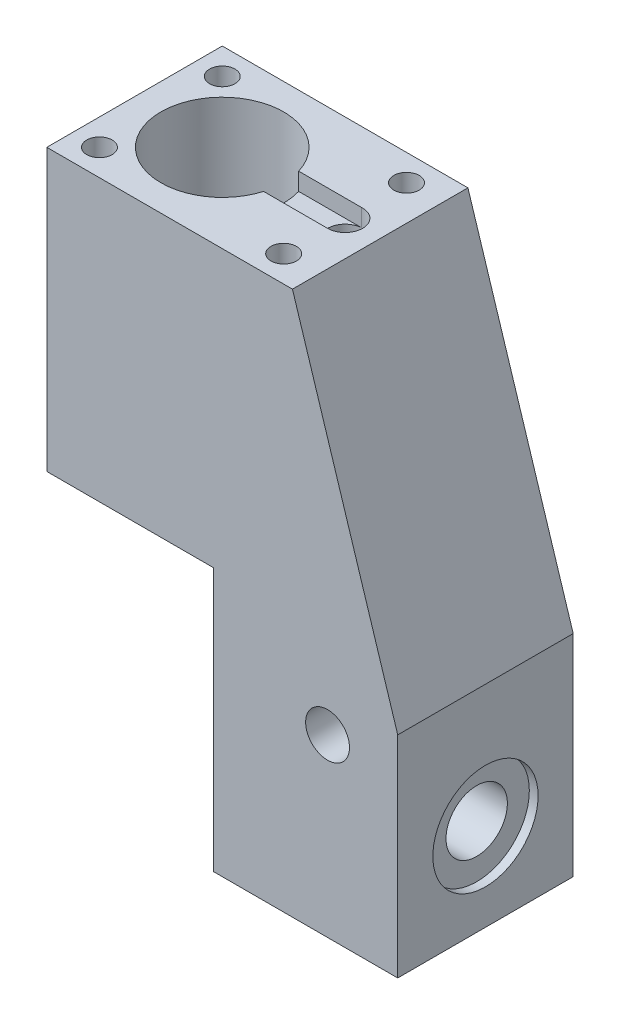
SolidWorks part; units mm, degrees
ref_plane "Front Plane" through (0, 0, 0) normal (0, 0, 1) x (1, 0, 0)
ref_plane "Top Plane" through (0, 0, 0) normal (0, 1, 0) x (1, 0, 0)
ref_plane "Right Plane" through (0, 0, 0) normal (1, 0, 0) x (0, 0, -1)
sketch "Sketch1" plane through (0, 0, 0) normal (0, 0, 1) x (1, 0, 0)
  line L0 (0, 0) -> (0, 24)
  line L1 (0, 24) -> (-12, 62)
  line L2 (-12, 62) -> (-40, 62)
  line L3 (-40, 62) -> (-40, 30)
  line L4 (-40, 30) -> (-21, 30)
  line L5 (-21, 30) -> (-21, 0)
  line L6 (-21, 0) -> (0, 0)
  dimension "D1" = 62
  dimension "D2" = 21
  dimension "D3" = 12
  dimension "D4" = 38
  dimension "D5" = 40
  dimension "D6" = 30
extrude "Boss-Extrude1" add sketch "Sketch1" along normal mid plane 20
sketch "Sketch2" plane through (0, 62, 0) normal (0, 1, 0) x (1, 0, 0)
  line L0 (-40, -10) -> (-40, 10) construction
  circle A0 centre (-30, 0) radius 7
  point P4 (-40, 0)
  dimension "D1" = 14
  dimension "D2" = 10
extrude "Cut-Extrude1" cut sketch "Sketch2" against normal up to next
hole_wizard "CSK for M8 Flat Head Machine Screw1" positions "Sketch4" profile "Sketch5" countersink size "M8" standard "ANSI Metric" end condition through all
sketch "Sketch4" plane through (0, 0, 0) normal (1, 0, 0) x (0, 0, -1)
  line L0 (-10, 0) -> (10, 0) construction
  point P0 (0, 10)
  dimension "D1" = 10
sketch "Sketch5" plane through (0, 10, 0) normal (0, 1, 0) x (0, 0, -1)
  line L0 (0, 0) -> (0, 40)
  line L1 (0, 40) -> (3.5, 40)
  line L2 (3.5, 40) -> (3.5, 0.5)
  line L3 (3.5, 0.5) -> (4, 0)
  line L5 (4, 0) -> (0, 0)
  line L6 (-3.5, 0.5) -> (-4, 0) construction
  line L11 (0, -6.35) -> (0, 107.95) construction
  dimension "Thru Hole Dia." = 7
  dimension "Thru Hole Depth" = 40
  dimension "Near C'Sink Dia." = 8
  dimension "Near C'Sink Angle" = 90
hole_wizard "M4x0.7 Tapped Hole1" positions "Sketch6" profile "Sketch7" tap size "M4x0.7" standard "ANSI Metric"
sketch "Sketch6" plane through (0, 0, 0) normal (0, -1, 0) x (-1, 0, 0)
  line L0 (0, -10) -> (0, 10) construction
  point P0 (8, 0)
  point P2 (16, 0)
  dimension "D1" = 8
  dimension "D2" = 8
sketch "Sketch7" plane through (-8, 0, 0) normal (1, 0, 0) x (0, 0, -1)
  line L0 (0, 0) -> (0, 6.5)
  line L1 (0, 6.5) -> (2, 6.5)
  line L2 (2, 6.5) -> (2, 0)
  line L5 (2, 0) -> (0, 0)
  line L11 (0, -6.35) -> (0, 107.95) construction
  dimension "Thru Tap Drill Dia." = 4
  dimension "Thru Tap Drill Depth" = 6.5
cosmetic thread "Hole Thread1" parameters "D2"=4
cosmetic thread "Hole Thread2" parameters "D2"=4
sketch "Sketch8" plane through (0, 0, 10) normal (0, 0, 1) x (1, 0, 0)
  line L0 (0, 0) -> (0, 24) construction
  line L1 (-21, 0) -> (0, 0) construction
  circle A0 centre (-8, 20) radius 2.5
  dimension "D1" = 5
  dimension "D3" = 20
  dimension "D2" = 8
extrude "Cut-Extrude2" cut sketch "Sketch8" against normal up to next
sketch "Sketch9" plane through (0, 0, 0) normal (0, -1, 0) x (1, 0, 0)
  circle A0 centre (-8, 0) radius 1.25
  dimension "D1" = 2.5
extrude "Cut-Extrude3" cut sketch "Sketch9" against normal up to next
hole_wizard "Tap Drill for M3.5x0.6 Tap1" positions "Sketch13" profile "Sketch12" hole size "M3.5x0.6" standard "ANSI Metric"
sketch "Sketch13" plane through (0, 62, 0) normal (0, 1, 0) x (1, 0, 0)
  line L0 (-40, -10) -> (-40, 10) construction
  line L1 (-12, 10) -> (-40, 10) construction
  point P0 (-37, 7)
  point P2 (-16, 7)
  point P4 (-16, -7)
  point P6 (-37, -7)
  dimension "D1" = 3
  dimension "D2" = 24
  dimension "D3" = 14
  dimension "D4" = 3
sketch "Sketch12" plane through (-37, 62, -7) normal (1, 0, 0) x (0, 0, 1)
  line L0 (0, 0) -> (0, 9.8712)
  line L1 (0, 9.8712) -> (1.45, 9)
  line L2 (1.45, 9) -> (1.45, 0)
  line L5 (1.45, 0) -> (0, 0)
  line L10 (0, 9.8712) -> (-1.45, 9) construction
  line L11 (0, -6.35) -> (0, 107.95) construction
  dimension "Hole Dia." = 2.9
  dimension "Hole Depth" = 9
  dimension "Drill Angle" = 118
sketch "Sketch14" plane through (-40, 0, 0) normal (-1, 0, 0) x (0, 0, 1)
  line L0 (10, 62) -> (-10, 62) construction
  line L1 (-10, 62) -> (-10, 30) construction
  circle A0 centre (-3, 45) radius 1.6
  circle A1 centre (3, 45) radius 1.6
  dimension "D1" = 3.2
  dimension "D2" = 17
  dimension "D3" = 6
  dimension "D4" = 7
extrude "Cut-Extrude4" cut sketch "Sketch14" against normal up to next
hole_wizard "CBORE for M4 Cross Recess Pan Head Screw1" positions "Sketch15" profile "Sketch16" counterbore size "M4" standard "IS" end condition up to next
sketch "Sketch15" plane through (0, 62, 0) normal (0, 1, 0) x (1, 0, 0)
  point P0 (-16, 0)
  dimension "D1" = 24
sketch "Sketch16" plane through (-16, 62, 0) normal (1, 0, 0) x (0, 0, 1)
  line L0 (0, 0) -> (0, 48.5)
  line L1 (0, 48.5) -> (1.25, 48.5)
  line L3 (1.25, 48.5) -> (1.25, 30)
  line L4 (1.25, 30) -> (2, 30)
  line L5 (2, 30) -> (2, 0)
  line L7 (2, 0) -> (0, 0)
  line L11 (0, -6.35) -> (0, 107.95) construction
  dimension "Thru Hole Dia." = 2.5
  dimension "Thru Hole Depth" = 48.5
  dimension "C'Bore Dia." = 4
  dimension "C'Bore Depth" = 30
sketch "Sketch17" plane through (0, 62, 0) normal (0, 1, 0) x (1, 0, 0)
  line L0 (-16.1101, 2) -> (-23.2918, 2)
  line L1 (-16.1101, -2) -> (-23.2918, -2)
  line L2 (-16.1101, 2) -> (-16.1101, -2)
  circle A0 centre (-30, 0) radius 7 construction
  circle A1 centre (-30, 0) radius 7
  point P8 (-16.1101, 0)
  circle M7 centre (-30, 0) radius 7
  circle M12 centre (-16, 0) radius 2
  dimension "D1" = 4
extrude "Cut-Extrude5" cut sketch "Sketch17" against normal blind 2 contours L2 L0 L1 M7 M12
sketch "Sketch18" plane through (0, 0, 0) normal (1, 0, 0) x (0, 0, -1)
  circle A0 centre (0, 10) radius 6
  dimension "D1" = 12
extrude "Cut-Extrude6" cut sketch "Sketch18" against normal blind 1
chamfer "Chamfer1" distance 0.5 angle 45 1 edges at (-21, 13.5, 0)
